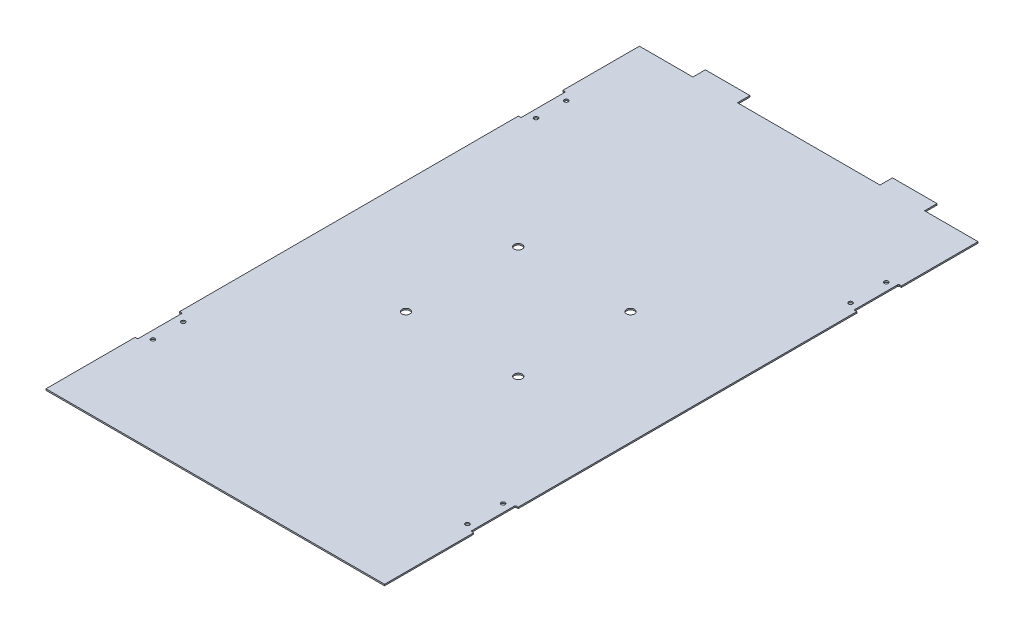
SolidWorks part; units mm, degrees
ref_plane "Front Plane" through (0, 0, 0) normal (0, 0, 1) x (1, 0, 0)
ref_plane "Top Plane" through (0, 0, 0) normal (0, 1, 0) x (1, 0, 0)
ref_plane "Right Plane" through (0, 0, 0) normal (1, 0, 0) x (0, 0, -1)
sketch "Sketch1" plane through (0, 0, 0) normal (0, 1, 0) x (1, 0, 0)
  line L0 (65.3263, 149.0698) -> (95.3263, 149.0698)
  line L1 (-94.6737, 149.0698) -> (-64.6737, 149.0698)
  line L2 (-94.6737, 149.0698) -> (-94.6737, -183.9302)
  line L3 (-94.6737, -183.9302) -> (95.3263, -183.9302)
  line L4 (95.3263, 149.0698) -> (95.3263, -183.9302)
  line L6 (-64.6737, 149.0698) -> (-64.6737, 156.0698)
  line L7 (-64.6737, 156.0698) -> (-39.6737, 156.0698)
  line L8 (-39.6737, 149.0698) -> (-39.6737, 156.0698)
  line L10 (65.3263, 149.0698) -> (65.3263, 156.0698)
  line L11 (65.3263, 156.0698) -> (40.3263, 156.0698)
  line L12 (40.3263, 149.0698) -> (40.3263, 156.0698)
  line L13 (-39.6737, 149.0698) -> (40.3263, 149.0698)
  point P4 (-64.6737, 149.0698)
  point P5 (-94.6737, 149.0698)
  point P15 (65.3263, 149.0698)
  point P16 (40.3263, 149.0698)
  dimension "D1" = 333
  dimension "D2" = 190
  dimension "D3" = 7
  dimension "D4" = 7
  dimension "D5" = 30
  dimension "D6" = 30
  dimension "D7" = 25
  dimension "D8" = 25
extrude "Panel" add sketch "Sketch1" along normal blind 0.79
ref_plane "Length" through (0.3263, 0, 0) normal (-1, 0, 0) x (0, 0, 1)
ref_plane "Width " through (0, 0, 13.9302) normal (0, 0, 1) x (1, 0, 0)
sketch "Sketch3" plane through (0, 0.79, 0) normal (0, 1, 0) x (1, 0, 0)
  line L0 (-94.6737, 149.0698) -> (-94.6737, -183.9302) construction
  line L1 (-94.6737, -108.9302) -> (-84.6737, -108.9302) construction
  line L2 (-94.6737, -108.9302) -> (-94.6737, -133.9302) construction
  line L3 (-94.6737, -133.9302) -> (-84.6737, -133.9302) construction
  line L4 (-84.6737, -108.9302) -> (-84.6737, -133.9302) construction
  line L5 (-94.6737, -183.9302) -> (95.3263, -183.9302) construction
  line L7 (-94.6737, -108.9302) -> (-93.6737, -108.9302)
  line L8 (-94.6737, -108.9302) -> (-94.6737, -133.9302)
  line L9 (-94.6737, -133.9302) -> (-93.6737, -133.9302)
  line L10 (-93.1737, -109.4302) -> (-93.1737, -133.4302)
  circle A0 centre (-88.6737, -112.9302) radius 1.125
  circle A1 centre (-88.6737, -129.9302) radius 1.125
  arc A2 (-93.6737, -133.9302) -> (-93.1737, -133.4302) centre (-93.6737, -133.4302) ccw
  arc A3 (-93.1737, -109.4302) -> (-93.6737, -108.9302) centre (-93.6737, -109.4302) ccw
  point P0 (-94.6737, 149.0698)
  point P18 (-93.1737, -133.9302)
  point P21 (-93.1737, -108.9302)
  dimension "D5" = 2.25
  dimension "D9" = 2.25
  dimension "D11" = 0.5
  dimension "D1" = 50
  dimension "D2" = 10
  dimension "D3" = 4
  dimension "D4" = 4
  dimension "D6" = 25
  dimension "D7" = 4
  dimension "D8" = 4
  dimension "D10" = 1.5
extrude "Outer Hinge Mount" cut sketch "Sketch3" against normal blind 0.79
mirror "Mirror1" about plane through (0, 0, 13.9302) normal (0, 0, 1) of "Outer Hinge Mount"
sketch "Sketch4" plane through (0, 0.79, 0) normal (0, 1, 0) x (1, 0, 0)
  line L0 (-0.4345, -13.9302) -> (0.4345, -13.9302) construction
  line L1 (0.3263, 0.4345) -> (0.3263, -0.4345) construction
  line L2 (0.3263, -13.9302) -> (0.3263, 35.2823) construction
  line L4 (0.3263, 30.6214) -> (-31.1765, 17.5725) construction
  line L5 (-31.1765, 17.5725) -> (-44.2253, -13.9302) construction
  line L6 (-44.2253, -13.9302) -> (-31.1765, -45.4329) construction
  line L7 (-31.1765, -45.4329) -> (0.3263, -58.4818) construction
  line L8 (0.3263, -58.4818) -> (31.829, -45.4329) construction
  line L9 (31.829, -45.4329) -> (44.8779, -13.9302) construction
  line L10 (44.8779, -13.9302) -> (31.829, 17.5725) construction
  line L11 (31.829, 17.5725) -> (0.3263, 30.6214) construction
  circle A0 centre (0.3263, -13.9302) radius 49.2125 construction
  circle A1 centre (0.3263, -13.9302) radius 41.1603 construction
  circle A2 centre (-31.1765, 17.5725) radius 2.25
  circle A3 centre (31.829, 17.5725) radius 2.25
  circle A4 centre (31.829, -45.4329) radius 2.25
  circle A5 centre (-31.1765, -45.4329) radius 2.25
  point P0 (0.3263, -13.9302)
  point P1 (0.3263, 35.2823)
  dimension "D1" = 98.425
  dimension "D3" = 4.5
  dimension "D4" = 4.5
  dimension "D5" = 4.5
  dimension "D6" = 4.5
  dimension "D2" = 44.5516
extrude "Mounting Plate Holes" cut sketch "Sketch4" against normal blind 10
sketch "Sketch5" plane through (0, 0.79, 0) normal (0, 1, 0) x (1, 0, 0)
  text T0 "Middle Panel \r\nInner Face\r\n (Reflectarray)" font "Century Gothic" height 10
  text T1 "Inner Panel"
  text T2 "Outer Panel\r\n"
sketch "Sketch6" plane through (0, 0.79, 0) normal (0, 1, 0) x (1, 0, 0)
  line L0 (95.3263, -183.9302) -> (95.3263, 149.0698) construction
  line L1 (-94.6737, -183.9302) -> (95.3263, -183.9302) construction
  line L3 (95.3263, -133.9302) -> (80.3263, -133.9302) construction
  line L4 (95.3263, -133.9302) -> (95.3263, -108.9302) construction
  line L5 (95.3263, -108.9302) -> (80.3263, -108.9302) construction
  line L6 (80.3263, -133.9302) -> (80.3263, -108.9302) construction
  line L7 (95.3263, -108.9302) -> (94.2463, -108.9302)
  line L8 (95.3263, -108.9302) -> (95.3263, -133.9302)
  line L9 (95.3263, -133.9302) -> (94.2463, -133.9302)
  line L10 (93.7463, -109.4302) -> (93.7463, -133.4302)
  line L11 (95.3263, 106.0698) -> (80.3263, 106.0698) construction
  line L12 (95.3263, 106.0698) -> (95.3263, 81.0698) construction
  line L13 (95.3263, 81.0698) -> (80.3263, 81.0698) construction
  line L14 (80.3263, 106.0698) -> (80.3263, 81.0698) construction
  line L15 (95.3263, 106.0698) -> (94.2463, 106.0698)
  line L16 (95.3263, 106.0698) -> (95.3263, 81.0698)
  line L17 (95.3263, 81.0698) -> (94.2463, 81.0698)
  line L18 (93.7463, 105.5698) -> (93.7463, 81.5698)
  arc A0 (93.7463, -133.4302) -> (94.2463, -133.9302) centre (94.2463, -133.4302) ccw
  circle A1 centre (85.3263, -111.4302) radius 1
  circle A2 centre (90.3263, -131.4302) radius 1
  arc A3 (93.7463, -109.4302) -> (94.2463, -108.9302) centre (94.2463, -109.4302) cw
  circle A4 centre (85.3263, 103.5698) radius 1
  circle A5 centre (90.3263, 83.5698) radius 1
  arc A6 (93.7463, 105.5698) -> (94.2463, 106.0698) centre (94.2463, 105.5698) cw
  arc A7 (93.7463, 81.5698) -> (94.2463, 81.0698) centre (94.2463, 81.5698) ccw
  point P0 (95.3263, -133.9302)
  point P9 (90.3263, -131.4302)
  point P10 (85.3263, -111.4302)
  point P15 (93.7463, -133.9302)
  point P22 (95.3263, 149.0698)
  point P28 (90.3263, 83.5698)
  point P29 (85.3263, 103.5698)
  point P40 (93.7463, 81.0698)
  dimension "D9" = 0.5
  dimension "D10" = 2
  dimension "D11" = 2
  dimension "D12" = 0.5
  dimension "D20" = 2
  dimension "D21" = 2
  dimension "D23" = 0.5
  dimension "D24" = 0.5
  dimension "D1" = 50
  dimension "D2" = 15
  dimension "D3" = 25
  dimension "D4" = 2.5
  dimension "D5" = 2.5
  dimension "D6" = 10
  dimension "D7" = 5
  dimension "D8" = 1.58
  dimension "D13" = 43
  dimension "D14" = 25
  dimension "D15" = 15
  dimension "D16" = 2.5
  dimension "D17" = 2.5
  dimension "D18" = 5
  dimension "D19" = 10
  dimension "D22" = 1.58
extrude "Cut-Extrude1" [suppressed] cut sketch "Sketch6" against normal blind 10
mirror "Mirror2" [suppressed] about plane through (0.3263, 0, 0) normal (-1, 0, 0)
sketch "Sketch7" plane through (0, 0.79, 0) normal (0, 1, 0) x (1, 0, 0)
  line L0 (95.3263, -183.9302) -> (95.3263, 149.0698) construction
  line L1 (-94.6737, -183.9302) -> (95.3263, -183.9302) construction
  line L2 (95.3263, -133.9302) -> (85.3263, -133.9302) construction
  line L3 (95.3263, -133.9302) -> (95.3263, -108.9302) construction
  line L4 (95.3263, -108.9302) -> (85.3263, -108.9302) construction
  line L5 (85.3263, -133.9302) -> (85.3263, -108.9302) construction
  line L6 (95.3263, -108.9302) -> (94.2463, -108.9302)
  line L7 (95.3263, -108.9302) -> (95.3263, -133.9302)
  line L8 (95.3263, -133.9302) -> (94.3802, -133.9302)
  line L9 (93.7463, -109.4302) -> (93.7463, -133.2963)
  circle A0 centre (89.3263, -111.4302) radius 1.125
  circle A1 centre (89.3263, -131.4302) radius 1.125
  arc A2 (93.7463, -109.4302) -> (94.2463, -108.9302) centre (94.2463, -109.4302) cw
  arc A3 (93.7463, -133.2963) -> (94.3802, -133.9302) centre (94.3802, -133.2963) ccw
  point P0 (95.3263, -183.9302)
  point P1 (95.3263, -133.9302)
  point P9 (89.3263, -111.4302)
  point P10 (89.3263, -131.4302)
  point P21 (93.7463, -133.9302)
  dimension "D7" = 2.25
  dimension "D8" = 2.25
  dimension "D9" = 0.5
  dimension "D10" = 0.6339
  dimension "D1" = 25
  dimension "D2" = 10
  dimension "D3" = 2.5
  dimension "D4" = 4
  dimension "D5" = 2.5
  dimension "D6" = 4
  dimension "D11" = 1.58
  dimension "D12" = 50
extrude "New Inner Hinge Mount" cut sketch "Sketch7" against normal blind 10
mirror "Mirror3" about plane through (0, 0, 13.9302) normal (0, 0, 1) of "New Inner Hinge Mount"
